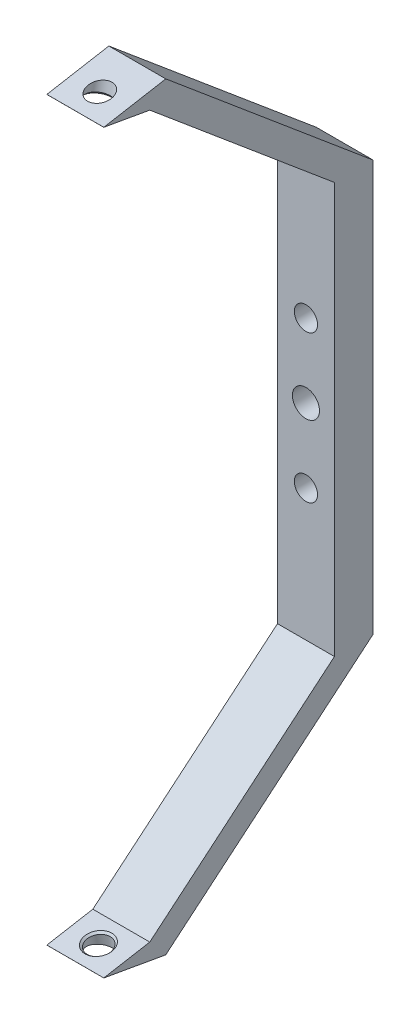
SolidWorks part; units mm, degrees
ref_plane "Plan de face" through (0, 0, 0) normal (0, 0, 1) x (1, 0, 0)
ref_plane "Plan de dessus" through (0, 0, 0) normal (0, 1, 0) x (1, 0, 0)
ref_plane "Plan de droite" through (0, 0, 0) normal (1, 0, 0) x (0, 0, -1)
sketch "Esquisse1" plane through (0, 0, 0) normal (0, 0, 1) x (1, 0, 0)
  line L13 (-3.675, 26.5) -> (3.675, 26.5)
  line L14 (-3.675, 26.5) -> (-3.675, -26.5)
  line L15 (-3.675, -26.5) -> (3.675, -26.5)
  line L16 (3.675, 26.5) -> (3.675, -26.5)
  line L17 (-3.675, 26.5) -> (3.675, -26.5) construction
  line L18 (-3.675, -26.5) -> (3.675, 26.5) construction
  point P0 (0, 0)
  dimension "D1" = 7.35
  dimension "D2" = 53
extrude "Boss.-Extru.1" add sketch "Esquisse1" along normal blind 5
sketch3d "Esquisse3D1"
  line L0 (0, 0, 0) -> (0, 0, 11.0766) construction
  point P3 (0, 0, 0)
  point P4 (0, 0, 11.0766)
sketch "Esquisse3" plane through (0, 0, 0) normal (0, 0, -1) x (-1, 0, 0)
  circle A0 centre (0, 9.5) radius 1.5
  circle A1 centre (0, -9.5) radius 1.5
extrude "Enlèv. mat.-Extru.1" cut sketch "Esquisse3" against normal through all
sketch "Esquisse4" plane through (0, 0, 5) normal (0, 0, 1) x (1, 0, 0)
  circle A0 centre (0, 0) radius 1.75
  dimension "D1" = 3.5
extrude "Enlèv. mat.-Extru.2" cut sketch "Esquisse4" against normal through all
sketch "Esquisse5" plane through (-3.675, 0, 0) normal (-1, 0, 0) x (0, 0, 1)
  line L0 (5, -26.5) -> (28.8351, -46.5)
  line L1 (28.8351, -46.5) -> (26.7692, -48.962)
  line L2 (26.7692, -48.962) -> (0, -26.5)
  line L3 (0, -26.5) -> (5, -26.5)
  dimension "D1" = 140
  dimension "D2" = 20
extrude "Boss.-Extru.2" add sketch "Esquisse5" against normal through all contours L3 L0 L1 L2
sketch "Esquisse7" plane through (0, -15.5508, -13.0487) normal (0, -0.766, -0.6428) x (1, 0, 0)
  line L0 (-3.675, 51.9786) -> (-3.675, 61.9786)
  line L1 (3.675, 51.9786) -> (3.675, 61.9786)
  arc A0 (-3.675, 61.9786) -> (3.675, 61.9786) centre (0, 61.9786) cw
  circle A1 centre (0, 61.9786) radius 1.5
  dimension "D2" = 3
  dimension "D1" = 10
sketch "Esquisse8" plane through (-3.675, 0, 0) normal (-1, 0, 0) x (0, 0, 1)
  line L0 (26.7692, -48.962) -> (34.7692, -47.5514)
  line L1 (28.8351, -46.5) -> (34.7692, -47.5463)
  line L2 (28.8351, -46.5) -> (26.7692, -48.962) construction
  line L3 (28.8351, -46.5) -> (26.7692, -48.962)
  arc A0 (34.7692, -47.5463) -> (34.7692, -47.5514) centre (34.7687, -47.5489) cw
  dimension "D1" = 8
  dimension "D2" = 40
extrude "Boss.-Extru.4" add sketch "Esquisse8" against normal up to surface (7.35 mm away) contours L3 L0 A0 L1 up to face at (3.675, -15.9103, 10.934)
sketch "Esquisse10" plane through (0, -40.1668, -7.0825) normal (0, 0.9848, 0.1736) x (1, 0, 0)
  line L0 (3.675, -36.4716) -> (-3.675, -36.4716) construction
  circle A0 centre (0, -39.4716) radius 1.5
  dimension "D1" = 3
  dimension "D2" = 3
extrude "Enlèv. mat.-Extru.4" cut sketch "Esquisse10" against normal up to surface (0.5606 mm away)
ref_plane "Plan1" through (0, 0, 0) normal (0, 1, 0) x (1, 0, 0)
sketch "Esquisse11" plane through (3.675, 0, 0) normal (1, 0, 0) x (0, 0, -1)
  line L0 (-5.7363, 0) -> (7.1001, 0) construction
  line L1 (2.75, 0) -> (-2.75, 0) construction
  line L2 (-26.7692, -48.962) -> (0, -26.5) construction
  line L3 (-34.7692, -47.5463) -> (-28.8351, -46.5) construction
  line L4 (-34.7692, -47.5514) -> (-26.7692, -48.962) construction
  line L5 (-5, -26.5) -> (-28.8351, -46.5) construction
  line L6 (-26.7692, -48.962) -> (0, -26.5)
  line L7 (-34.7692, -47.5463) -> (-28.8351, -46.5)
  line L8 (-34.7692, -47.5514) -> (-26.7692, -48.962)
  line L9 (-5, -26.5) -> (-28.8351, -46.5)
  line L10 (-26.7692, 48.962) -> (0, 26.5)
  line L11 (-34.7692, 47.5514) -> (-26.7692, 48.962)
  line L12 (-34.7692, 47.5463) -> (-28.8351, 46.5)
  line L13 (-5, 26.5) -> (-28.8351, 46.5)
  line L14 (-5, 26.5) -> (0, 26.5) construction
  line L15 (-5, 26.5) -> (0, 26.5)
  arc A0 (-34.7692, -47.5463) -> (-34.7692, -47.5514) centre (-34.7687, -47.5489) ccw construction
  arc A1 (-34.7692, -47.5463) -> (-34.7692, -47.5514) centre (-34.7687, -47.5489) ccw
  arc A2 (-34.7692, 47.5463) -> (-34.7692, 47.5514) centre (-34.7687, 47.5489) cw
  line M7 (0, 26.5) -> (-5, 26.5)
extrude "Boss.-Extru.5" add sketch "Esquisse11" against normal blind 7.35 contours A2 L12 L13 L10 L11 M7
sketch "Esquisse12" plane through (0, 40.1668, -7.0825) normal (0, -0.9848, 0.1736) x (1, 0, 0)
  circle A0 centre (0, 39.4845) radius 1.5
  dimension "D1" = 3
extrude "Enlèv. mat.-Extru.5" cut sketch "Esquisse12" against normal blind 7.35
chamfer "Chanfrein2" distance 0.25 angle 45 2 edges at (0, -47.2814, 33.2667) (0, 46.7627, 30.3249)
